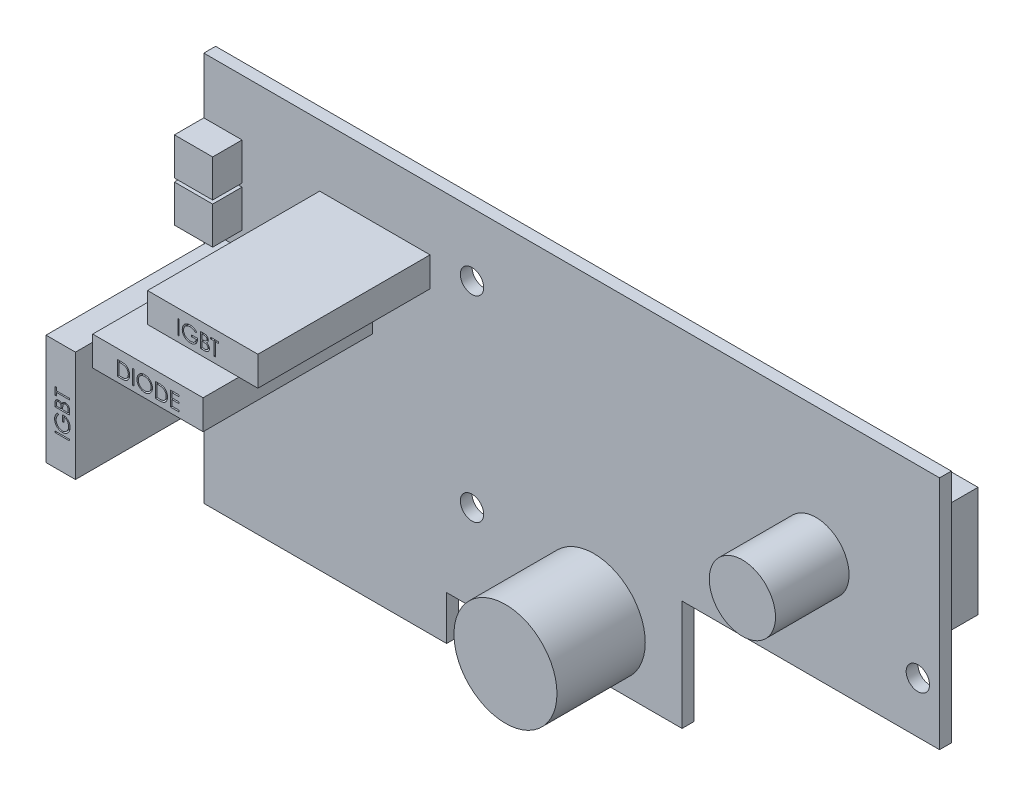
SolidWorks part; units mm, degrees
ref_plane "Front Plane" through (0, 0, 0) normal (0, 0, 1) x (1, 0, 0)
ref_plane "Top Plane" through (0, 0, 0) normal (0, 1, 0) x (1, 0, 0)
ref_plane "Right Plane" through (0, 0, 0) normal (1, 0, 0) x (0, 0, -1)
sketch "Sketch1" plane through (0, 0, 0) normal (0, 0, 1) x (1, 0, 0)
  line L0 (33, -53) -> (33, -47)
  line L1 (0, 0) -> (33, 0)
  line L2 (0, 0) -> (0, -53)
  line L3 (0, -53) -> (33, -53)
  line L4 (65, -47) -> (65, -32)
  line L5 (65, -47) -> (33, -47)
  line L7 (65, 0) -> (33, 0)
  line L9 (65, 0) -> (100, 0)
  line L11 (65, -32) -> (100, -32)
  line L12 (100, 0) -> (100, -32)
  dimension "D1" = 53
  dimension "D2" = 33
  dimension "D3" = 47
  dimension "D4" = 32
  dimension "D5" = 32
  dimension "D6" = 35
extrude "Boss-Extrude1" add sketch "Sketch1" along normal blind 1.6
sketch "Sketch2" plane through (0, 0, 0) normal (0, 0, -1) x (-1, 0, 0)
  line L0 (-100, 0) -> (0, 0) construction
  line L1 (-93.625, -10.1) -> (-88.625, -10.1)
  line L2 (-93.625, -10.1) -> (-93.625, -25.1)
  line L3 (-93.625, -25.1) -> (-88.625, -25.1)
  line L4 (-88.625, -10.1) -> (-88.625, -25.1)
  line L5 (-100, -32) -> (-100, 0) construction
  dimension "D1" = 5
  dimension "D2" = 15
  dimension "D3" = 10.1
  dimension "D4" = 6.375
extrude "Boss-Extrude2" add sketch "Sketch2" along normal blind 10
sketch "Sketch3" plane through (0, 0, 1.6) normal (0, 0, 1) x (1, 0, 0)
  line L0 (100, -32) -> (100, 0) construction
  line L1 (65, -32) -> (100, -32) construction
  line L2 (100, 0) -> (0, 0) construction
  circle A0 centre (97.05, -25.05) radius 1.5875
  circle A1 centre (36.45, -8.6) radius 1.5875
  circle A2 centre (36.45, -35.276) radius 1.5875
  dimension "D1" = 3.175
  dimension "D2" = 3.175
  dimension "D3" = 3.175
  dimension "D4" = 2.95
  dimension "D5" = 6.95
  dimension "D6" = 63.55
  dimension "D7" = 63.55
  dimension "D8" = 8.6
  dimension "D9" = 35.276
extrude "Cut-Extrude1" cut sketch "Sketch3" against normal through all
sketch "Sketch4" plane through (0, 0, 1.6) normal (0, 0, 1) x (1, 0, 0)
  line L0 (100, -32) -> (100, 0) construction
  line L1 (65, -32) -> (100, -32) construction
  circle A0 centre (83.2, -17.55) radius 4.5
  dimension "D1" = 9
  dimension "D2" = 16.8
  dimension "D3" = 14.45
extrude "Boss-Extrude3" add sketch "Sketch4" along normal blind 10
sketch "Sketch5" plane through (0, 0, 1.6) normal (0, 0, 1) x (1, 0, 0)
  line L0 (65, -47) -> (65, -32) construction
  line L1 (33, -47) -> (65, -47) construction
  circle A0 centre (53, -39.4) radius 7
  dimension "D3" = 14
  dimension "D1" = 12
  dimension "D2" = 7.6
extrude "Boss-Extrude4" add sketch "Sketch5" along normal blind 12
sketch "Sketch6" plane through (0, 0, 1.6) normal (0, 0, 1) x (1, 0, 0)
  line L0 (100, 0) -> (0, 0) construction
  line L1 (15.75, -8.374) -> (30.75, -8.374)
  line L2 (15.75, -8.374) -> (15.75, -12.374)
  line L3 (15.75, -12.374) -> (30.75, -12.374)
  line L4 (30.75, -8.374) -> (30.75, -12.374)
  line L9 (1.95, -20.526) -> (5.95, -20.526)
  line L10 (1.95, -20.526) -> (1.95, -35.526)
  line L11 (1.95, -35.526) -> (5.95, -35.526)
  line L12 (5.95, -20.526) -> (5.95, -35.526)
  line L13 (0, 0) -> (0, -53) construction
  dimension "D1" = 8.374
  dimension "D2" = 15.75
  dimension "D3" = 15
  dimension "D4" = 4
  dimension "D7" = 15
  dimension "D8" = 4
  dimension "D9" = 1.95
  dimension "D10" = 20.526
extrude "Boss-Extrude5" add sketch "Sketch6" along normal blind 23.4
sketch "Sketch7" plane through (0, 0, 25) normal (0, 0, 1) x (1, 0, 0)
  line L0 (19.621, -11.5846) -> (28.2327, -11.5846) construction
  text T0 "IGBT" font "Century Gothic" height 2
sketch "Sketch8" plane through (0, 0, 25) normal (0, 0, 1) x (1, 0, 0)
  line L0 (5.1709, -31.6306) -> (5.1709, -24.2451) construction
  text T0 "IGBT" font "Century Gothic" height 2
extrude "Cut-Extrude2" cut sketch "Sketch7" against normal blind 1
extrude "Cut-Extrude3" cut sketch "Sketch8" against normal blind 1
sketch "Sketch9" plane through (0, 0, 1.6) normal (0, 0, 1) x (1, 0, 0)
  line L0 (0, 0) -> (0, -53) construction
  line L1 (7.9, -17.625) -> (22.9, -17.625)
  line L2 (7.9, -17.625) -> (7.9, -21.625)
  line L3 (7.9, -21.625) -> (22.9, -21.625)
  line L4 (22.9, -17.625) -> (22.9, -21.625)
  line L5 (100, 0) -> (0, 0) construction
  dimension "D1" = 15
  dimension "D2" = 4
  dimension "D3" = 7.9
  dimension "D4" = 17.625
extrude "Boss-Extrude6" add sketch "Sketch9" along normal blind 23
sketch "Sketch10" plane through (0, 0, 24.6) normal (0, 0, 1) x (1, 0, 0)
  line L0 (11.0137, -20.9289) -> (20.6401, -20.9289) construction
  text T0 "DIODE" font "Century Gothic" height 2
extrude "Cut-Extrude4" cut sketch "Sketch10" against normal blind 1
sketch "Sketch11" plane through (0, 0, 1.6) normal (0, 0, 1) x (1, 0, 0)
  line L0 (100, 0) -> (0, 0) construction
  line L1 (5.2, -7.625) -> (0, -7.625)
  line L2 (5.2, -7.625) -> (5.2, -12.7)
  line L3 (5.2, -12.7) -> (0, -12.7)
  line L4 (0, -7.625) -> (0, -12.7)
  line L5 (5.2, -13.175) -> (0, -13.175)
  line L6 (5.2, -13.175) -> (5.2, -18.25)
  line L7 (5.2, -18.25) -> (0, -18.25)
  line L8 (0, -13.175) -> (0, -18.25)
  line L9 (0, 0) -> (0, -53) construction
  dimension "D1" = 5.2
  dimension "D2" = 7.625
  dimension "D3" = 5.075
  dimension "D4" = 5.075
  dimension "D5" = 5.2
  dimension "D6" = 13.175
extrude "Boss-Extrude7" add sketch "Sketch11" along normal blind 4
sketch "Sketch12" plane through (0, 0, 0) normal (-1, 0, 0) x (0, 0, 1)
  line L0 (2.3744, -8.0529) -> (2.3744, -12.1217) construction
  line L1 (2.3744, -13.7431) -> (2.3744, -17.3561) construction
  text T0 "CHP" font "Century Gothic" height 1.5
  text T1 "KCK" font "Century Gothic" height 1.5
extrude "Cut-Extrude5" cut sketch "Sketch12" against normal blind 1
